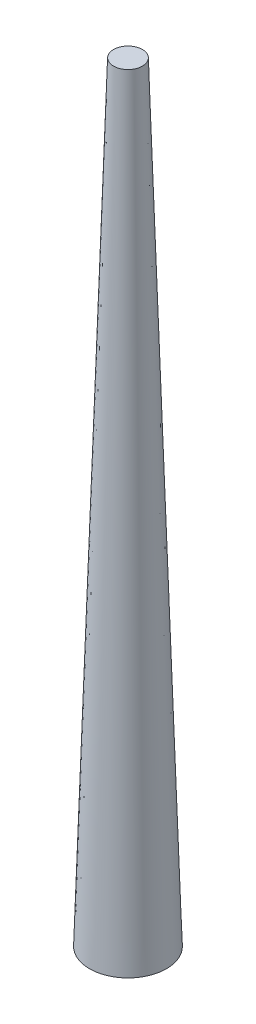
SolidWorks part; units mm, degrees
material "2014 Alloy"
ref_plane "Front Plane" through (0, 0, 0) normal (0, 0, 1) x (1, 0, 0)
ref_plane "Top Plane" through (0, 0, 0) normal (0, 1, 0) x (1, 0, 0)
ref_plane "Right Plane" through (0, 0, 0) normal (1, 0, 0) x (0, 0, -1)
sketch "Sketch2" plane through (0, 0, 0) normal (0, 0, 1) x (1, 0, 0)
  line L0 (0, 0) -> (-50.8, 0)
  line L1 (-50.8, 0) -> (-19.05, 1016)
  line L2 (-19.05, 1016) -> (0, 1016)
  line L3 (0, 1016) -> (0, 0)
revolve "Revolve4" add sketch "Sketch2" angle 360 about L3
